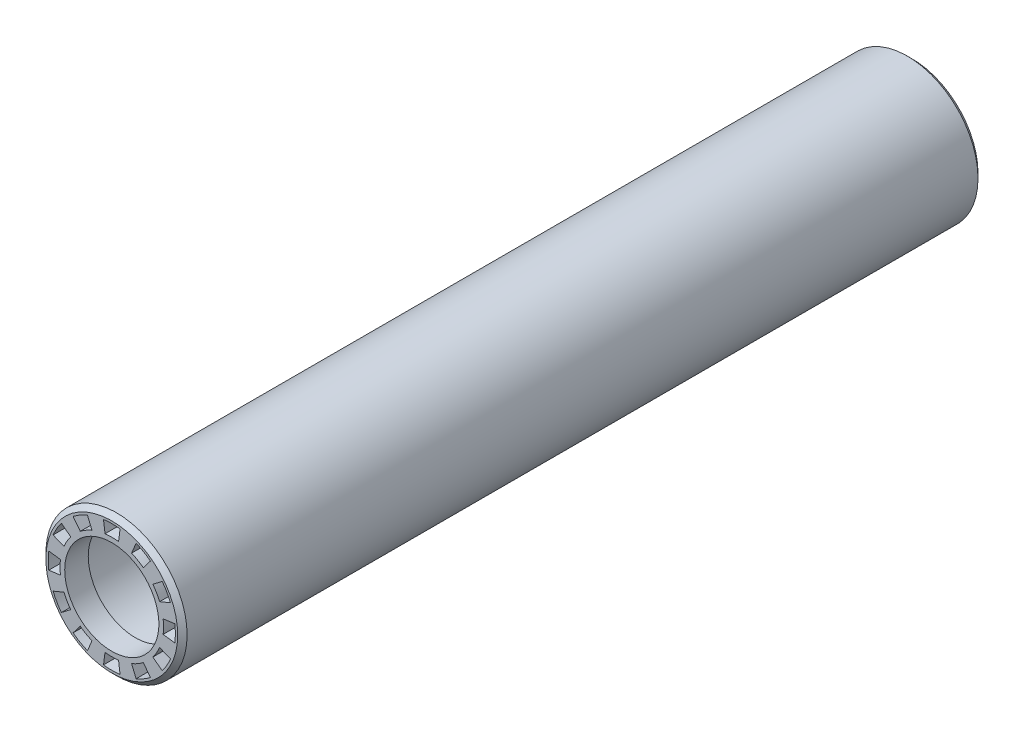
SolidWorks part; units mm, degrees
material "Rubber"
ref_plane "Front Plane" through (0, 0, 0) normal (0, 0, 1) x (1, 0, 0)
ref_plane "Top Plane" through (0, 0, 0) normal (0, 1, 0) x (1, 0, 0)
ref_plane "Right Plane" through (0, 0, 0) normal (1, 0, 0) x (0, 0, -1)
sketch "Sketch1" plane through (0, 0, 0) normal (0, 0, 1) x (1, 0, 0)
  circle A0 centre (0, 0) radius 12
  circle A1 centre (0, 0) radius 15
  dimension "D1" = 24
  dimension "D2" = 30
extrude "Boss-Extrude1" add sketch "Sketch1" along normal mid plane 170
chamfer "Chamfer1" distance 1 angle 45 2 edges at (15, 0, 85) (15, 0, -85)
sketch "Sketch2" plane through (0, 0, -85) normal (0, 0, -1) x (-1, 0, 0)
  circle A0 centre (0, 0) radius 10
  circle A1 centre (0, 0) radius 12
  circle A2 centre (0, 0) radius 12 construction
  dimension "D1" = 20
extrude "Boss-Extrude2" add sketch "Sketch2" against normal blind 5
mirror "Mirror1" about plane through (0, 0, 0) normal (0, 0, 1) of "Boss-Extrude2"
sketch "Sketch3" plane through (0, 0, -85) normal (0, 0, -1) x (-1, 0, 0)
  line L0 (-1.4358, 10.9059) -> (-1.7621, 13.3845)
  line L1 (0, 16.5) -> (0, -16.5) construction
  line L2 (1.4358, 10.9059) -> (1.7621, 13.3845)
  line L3 (0, 0) -> (-1.4358, 10.9059) construction
  line L4 (0, 0) -> (1.4358, 10.9059) construction
  arc A1 (1.4358, 10.9059) -> (-1.4358, 10.9059) centre (0, 0) ccw
  arc A2 (1.7621, 13.3845) -> (-1.7621, 13.3845) centre (0, 0) ccw
  arc A3 (-1.7621, 13.3845) -> (1.7621, 13.3845) centre (0, 0) ccw construction
  arc A4 (-1.4358, 10.9059) -> (1.4358, 10.9059) centre (0, 0) ccw construction
  dimension "D1" = 27
  dimension "D2" = 22
  dimension "D3" = 15
extrude "Cut-Extrude1" cut sketch "Sketch3" against normal blind 3
pattern_circular "CirPattern1" count 12 every 30 about axis through (0, 0, 0) along (0, 0, 1) of "Cut-Extrude1"
mirror "Mirror2" about plane through (0, 0, 0) normal (0, 0, 1) of "CirPattern1", "Cut-Extrude1"
